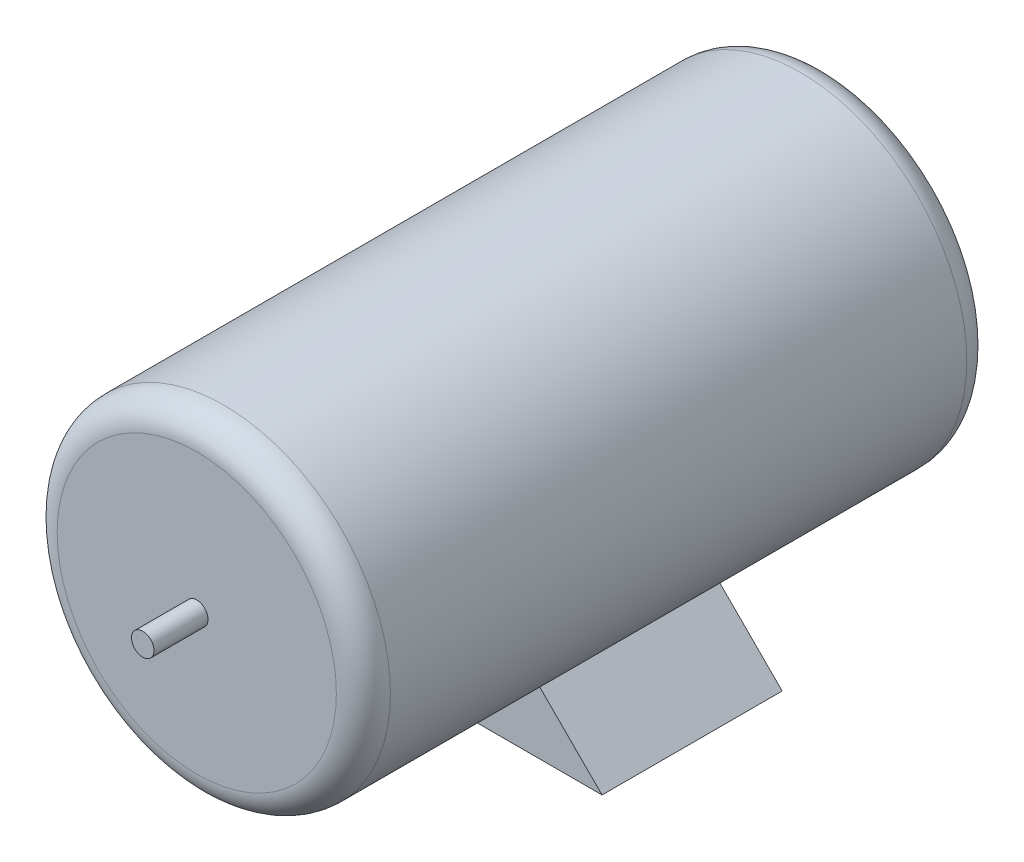
SolidWorks part; units mm, degrees
material "1060 Alloy"
ref_plane "Front Plane" through (0, 0, 0) normal (0, 0, 1) x (1, 0, 0)
ref_plane "Top Plane" through (0, 0, 0) normal (0, 1, 0) x (1, 0, 0)
ref_plane "Right Plane" through (0, 0, 0) normal (1, 0, 0) x (0, 0, -1)
sketch "Sketch1" plane through (0, 0, 0) normal (0, 0, 1) x (1, 0, 0)
  circle A0 centre (0, 0) radius 185
  dimension "D1" = 370
extrude "Boss-Extrude1" add sketch "Sketch1" along normal mid plane 700
fillet "Fillet1" radius 30 2 edges at (185, 0, -350) (185, 0, 350)
sketch "Sketch2" plane through (0, 0, 0) normal (0, 0, 1) x (1, 0, 0)
  line L0 (0, 0) -> (200, -200)
  line L1 (200, -200) -> (-200, -200)
  line L2 (-200, -200) -> (0, 0)
  point P3 (0, -200)
  dimension "D1" = 200
extrude "Boss-Extrude2" add sketch "Sketch2" along normal mid plane 200
sketch "Sketch3" plane through (0, 0, 350) normal (0, 0, 1) x (1, 0, 0)
  circle A0 centre (0, 0) radius 12.5
  dimension "D1" = 25
extrude "Boss-Extrude3" add sketch "Sketch3" along normal blind 60
